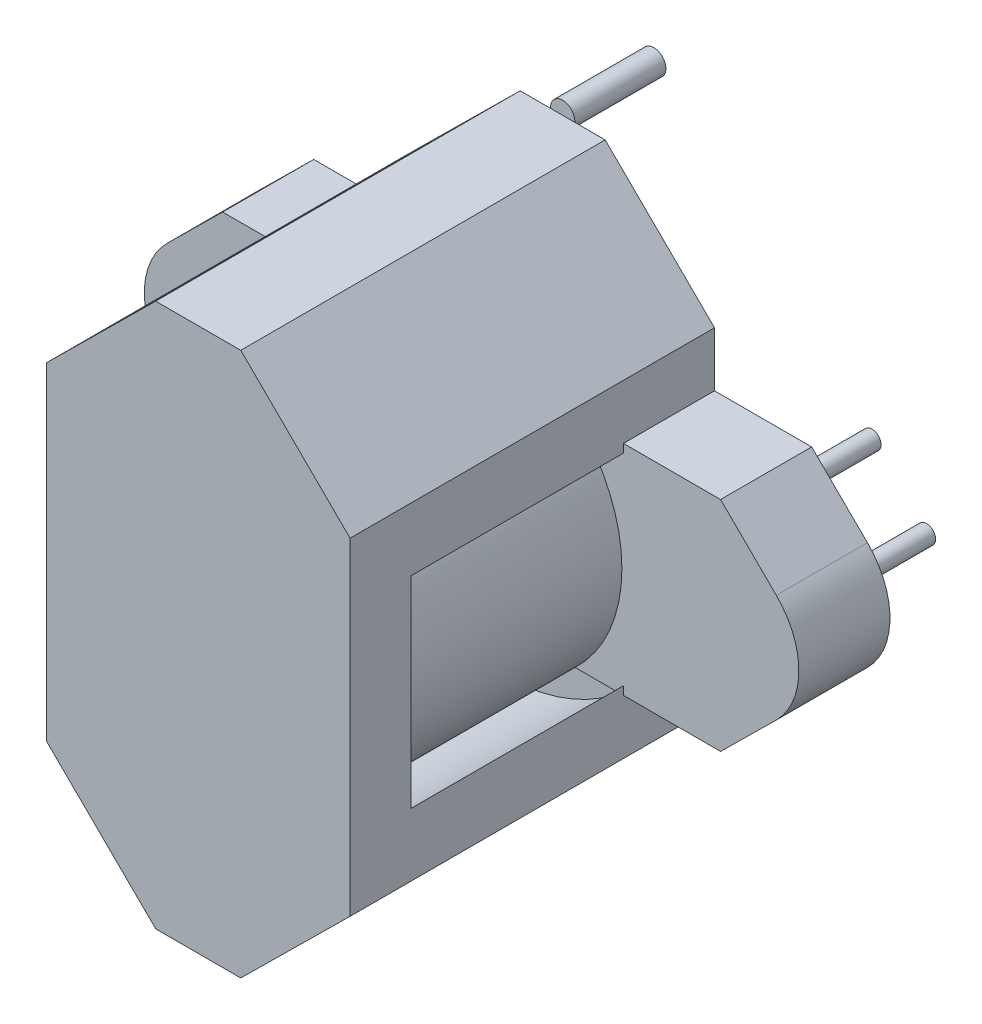
SolidWorks part; units mm, degrees
other "Детальный элемент1"
ref_plane "Спереди" through (0, 0, 0) normal (0, 0, 1) x (1, 0, 0)
ref_plane "Сверху" through (0, 0, 0) normal (0, 1, 0) x (1, 0, 0)
ref_plane "Справа" through (0, 0, 0) normal (1, 0, 0) x (0, 0, -1)
sketch "Эскиз1" plane through (0, 0, 0) normal (0, 0, 1) x (1, 0, 0)
  line L6 (0, 17.9) -> (2.8, 17.9)
  line L7 (2.8, 17.9) -> (6.4, 14.3423)
  line L8 (6.4, 14.3423) -> (6.4, 3.5577)
  line L9 (6.4, 3.5577) -> (2.8, 0)
  line L10 (2.8, 0) -> (0, 0)
  line L11 (0, 0) -> (-3.6, 3.5577)
  line L12 (-3.6, 3.5577) -> (-3.6, 14.3423)
  line L13 (-3.6, 14.3423) -> (0, 17.9)
  dimension "D1" = 10
  dimension "D2" = 14.7
  dimension "D3" = 17.9
  dimension "D4" = 2.8
extrude "Бобышка-Вытянуть1" add sketch "Эскиз1" along normal blind 2
sketch "Эскиз2" plane through (0, 0, 2) normal (0, 0, 1) x (1, 0, 0)
  line L0 (-3.6, 14.3423) -> (-3.6, 3.5577) construction
  line L1 (6.4, 3.5577) -> (6.4, 14.3423) construction
  line L2 (0, 0) -> (2.8, 0) construction
  line L3 (6.4, 5.6334) -> (6.4, 3.5577)
  line L4 (6.4, 3.5577) -> (2.8, 0)
  line L5 (2.8, 0) -> (0, 0)
  line L6 (0, 0) -> (-3.6, 3.5577)
  line L7 (-3.6, 3.5577) -> (-3.6, 5.6334)
  line L8 (-3.6, 12.2666) -> (-3.6, 14.3423)
  line L9 (-3.6, 14.3423) -> (0, 17.9)
  line L10 (0, 17.9) -> (-3.6, 14.3423) construction
  line L11 (0, 17.9) -> (2.8, 17.9)
  line L12 (2.8, 17.9) -> (6.4, 14.3423)
  line L13 (6.4, 14.3423) -> (6.4, 12.2666)
  arc A0 (-3.6, 5.6334) -> (6.4, 5.6334) centre (1.4, 8.95) ccw
  arc A1 (-3.6, 12.2666) -> (6.4, 12.2666) centre (1.4, 8.95) cw
  dimension "D2" = 6
  dimension "D4" = 6
  dimension "D1" = 5
  dimension "D3" = 8.95
extrude "Бобышка-Вытянуть2" add sketch "Эскиз2" along normal blind 8
sketch "Эскиз3" plane through (0, 0, 10) normal (0, 0, 1) x (1, 0, 0)
  line L0 (-3.6, 14.3423) -> (-3.6, 3.5577)
  line L1 (-3.6, 3.5577) -> (0, 0)
  line L2 (0, 0) -> (2.8, 0)
  line L3 (2.8, 0) -> (6.4, 3.5577)
  line L4 (6.4, 3.5577) -> (6.4, 14.3423)
  line L5 (6.4, 14.3423) -> (2.8, 17.9)
  line L6 (2.8, 17.9) -> (0, 17.9)
  line L7 (0, 17.9) -> (-3.6, 14.3423)
extrude "Бобышка-Вытянуть3" add sketch "Эскиз3" along normal blind 2
sketch "Эскиз4" plane through (0, 0, 2) normal (0, 0, 1) x (1, 0, 0)
  line L0 (6.4, 5.6334) -> (6.4, 12.2666) construction
  line L1 (0, 0) -> (2.8, 0) construction
  circle A0 centre (1.4, 8.95) radius 4.95
  dimension "D1" = 5
  dimension "D3" = 9.9
  dimension "D2" = 8.95
extrude "Бобышка-Вытянуть4" add sketch "Эскиз4" along normal blind 8
sketch "Эскиз5" plane through (0, 0, 0) normal (0, 0, 1) x (1, 0, 0)
  line L0 (-3.6, 14.3423) -> (-3.6, 3.5577) construction
  line L27 (9.5994, 12.5442) -> (-6.7968, 12.5442)
  line L28 (6.4, 14.3423) -> (2.8, 17.9) construction
  line L29 (0, 0) -> (2.8, 0) construction
  line L32 (-6.7968, 5.36) -> (9.5994, 5.36)
  line L33 (2.8, 0) -> (6.4, 3.5577) construction
  line L34 (6.4, 3.5577) -> (6.4, 14.3423) construction
  line L37 (-6.7968, 12.5442) -> (-8.6323, 10.7303)
  line L38 (-6.7968, 5.36) -> (-8.6323, 7.1739)
  line L39 (9.5994, 12.5442) -> (11.4349, 10.7303)
  line L40 (9.5994, 5.36) -> (11.4349, 7.1739)
  arc A0 (-8.6323, 10.7303) -> (-8.6323, 7.1739) centre (-6.875, 8.9521) ccw
  arc A1 (11.4349, 10.7303) -> (11.4349, 7.1739) centre (9.6776, 8.9521) cw
  point P16 (-9.375, 8.9521)
  point P17 (12.1776, 8.9521)
  dimension "D4" = 2.5
  dimension "D1" = 7.1842
  dimension "D2" = 21.5526
  dimension "D3" = 5.36
  dimension "D5" = 3.275
  dimension "D6" = 3.2776
extrude "Бобышка-Вытянуть5" add sketch "Эскиз5" along normal blind 3
ref_point "Точка1"
sketch "Эскиз6" plane through (0, 0, 0) normal (0, 0, 1) x (1, 0, 0)
  line L0 (6.4, 12.5442) -> (6.4, 14.3423) construction
  circle A0 centre (10.38, 8.9507) radius 0.3
  circle A1 centre (8.584, 10.7467) radius 0.3
  circle A2 centre (8.584, 7.1567) radius 0.3
  circle A3 centre (-5.784, 10.7467) radius 0.3
  circle A4 centre (-7.58, 8.9507) radius 0.3
  circle A5 centre (-5.784, 7.1567) radius 0.3
  circle A6 centre (1.4, 17.9307) radius 0.4
  circle A7 centre (1.4, -0.0293) radius 0.4
  dimension "D1" = 0.6
  dimension "D2" = 0.8
  dimension "D3" = 5
  dimension "D4" = 8.98
  dimension "D5" = 8.98
  dimension "D6" = 1.796
  dimension "D7" = 3.59
  dimension "D8" = 1.796
  dimension "D9" = 1.796
  dimension "D10" = 8.98
  dimension "D11" = 8.98
extrude "Бобышка-Вытянуть6" add sketch "Эскиз6" against normal blind 3
